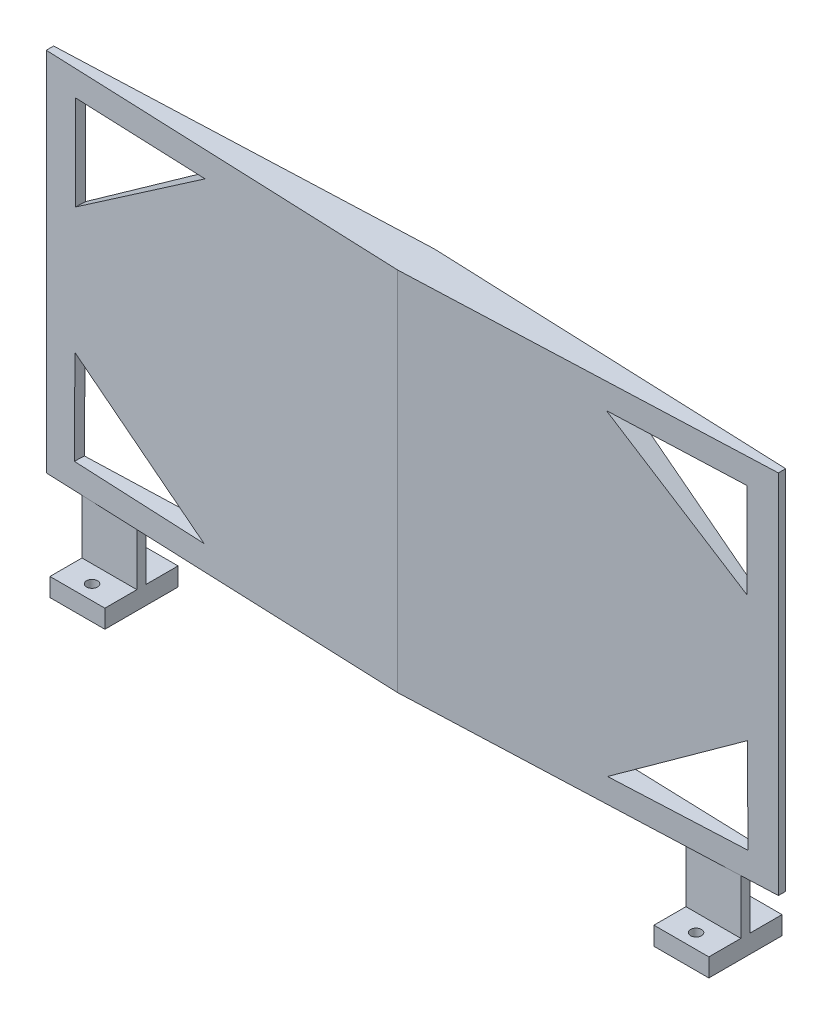
SolidWorks part; units mm, degrees
ref_plane "Front Plane" through (0, 0, 0) normal (0, 0, 1) x (1, 0, 0)
ref_plane "Top Plane" through (0, 0, 0) normal (0, 1, 0) x (1, 0, 0)
ref_plane "Right Plane" through (0, 0, 0) normal (1, 0, 0) x (0, 0, -1)
sketch "Sketch7" plane through (0, 0, 0) normal (0, 1, 0) x (1, 0, 0)
  line L0 (0, 0) -> (-100, 0) construction
  line L1 (-100, 0) -> (78.1251, 0) construction
  line L2 (0, 0) -> (0, 30.674) construction
  line L3 (0, 30.674) -> (0, -32.0574) construction
  line L5 (100, -1) -> (100, 1)
  line L6 (-100, 1) -> (0, 5)
  line L7 (-100, -1) -> (-100, 1)
  line L8 (-100, -1) -> (0, -5)
  line L10 (100, 1) -> (0, 5)
  line L11 (100, -1) -> (0, -5)
  dimension "D1" = 1
  dimension "D2" = 5
  dimension "D3" = 100
extrude "Boss-Extrude4" add sketch "Sketch7" along normal blind 100
sketch "Sketch8" plane through (0, 0, 0) normal (0, -1, 0) x (1, 0, 0)
  line L0 (-100, 0) -> (100, 0) construction
  line L1 (-100, -1) -> (-100, 1) construction
  line L2 (100, 1) -> (100, -1) construction
  line L3 (0, 5) -> (0, -5) construction
  line L9 (-90, 1.25) -> (-75, 1.25)
  line L10 (-90, 1.25) -> (-90, -1.25)
  line L11 (-90, -1.25) -> (-75, -1.25)
  line L12 (-75, 1.25) -> (-75, -1.25)
  line L13 (-90, 1.25) -> (-75, -1.25) construction
  line L14 (-90, -1.25) -> (-75, 1.25) construction
  point P10 (-82.5, 0)
  dimension "D1" = 17.5
  dimension "D2" = 2.5
  dimension "D3" = 15
extrude "Boss-Extrude5" add sketch "Sketch8" along normal blind 15
sketch "Sketch9" plane through (0, -15, 0) normal (0, -1, 0) x (1, 0, 0)
  line L0 (-90, 0) -> (-75, 0) construction
  line L1 (-90, 1.25) -> (-90, -1.25) construction
  line L2 (-75, -1.25) -> (-75, 1.25) construction
  line L3 (-82.5, 1.25) -> (-82.5, -1.25) construction
  line L4 (-75, 1.25) -> (-90, 1.25) construction
  line L5 (-90, -1.25) -> (-75, -1.25) construction
  line L7 (-90, 10) -> (-75, 10)
  line L8 (-90, 10) -> (-90, -10)
  line L9 (-90, -10) -> (-75, -10)
  line L10 (-75, 10) -> (-75, -10)
  line L11 (-90, 10) -> (-75, -10) construction
  line L12 (-90, -10) -> (-75, 10) construction
  point P12 (-82.5, 0)
  dimension "D1" = 15
  dimension "D2" = 20
extrude "Boss-Extrude6" add sketch "Sketch9" along normal blind 5
mirror "Mirror1" about plane through (0, 0, 0) normal (1, 0, 0) of "Boss-Extrude5", "Boss-Extrude6"
sketch "Sketch10" plane through (-0.1997, 0, 4.992) normal (-0.04, 0, 0.9992) x (0.9992, 0, 0.04)
  line L3 (-91.602, 67.2043) -> (-91.602, 93.0576)
  line L4 (-91.602, 93.0576) -> (-54.6698, 93.0576)
  line L5 (-54.6698, 93.0576) -> (-91.602, 67.2043)
  line L6 (0.1998, 99.3176) -> (0.1998, 0) construction
  line L7 (0.1998, 100) -> (0.1998, 0) construction
  line L8 (-99.8801, 50) -> (0.1998, 49.6588) construction
  line L9 (-99.8801, 100) -> (-99.8801, 0) construction
  line L10 (-91.8958, 6.8869) -> (-54.9644, 6.6351)
  line L11 (-91.7195, 32.7397) -> (-91.8958, 6.8869)
  line L12 (-54.9644, 6.6351) -> (-91.7195, 32.7397)
extrude "Cut-Extrude1" cut sketch "Sketch10" against normal up to surface (9.992 mm away)
mirror "Mirror2" about plane through (0, 0, 0) normal (1, 0, 0) of "Cut-Extrude1"
sketch "Sketch11" plane through (0, -15, 0) normal (0, 1, 0) x (1, 0, 0)
  line L0 (-82.5, 10) -> (-82.5, -10) construction
  line L1 (-90, 10) -> (-75, 10) construction
  line L2 (-75, -10) -> (-90, -10) construction
  circle A0 centre (-82.5, 6) radius 1.5
  dimension "D2" = 3
  dimension "D1" = 4
extrude "Cut-Extrude2" cut sketch "Sketch11" against normal up to surface (5 mm away) up to face at (-82.5, -20, 0)
mirror "Mirror3" about plane through (0, 0, 0) normal (0, 0, 1) of "Cut-Extrude2"
mirror "Mirror4" about plane through (0, 0, 0) normal (1, 0, 0) of "Mirror3", "Cut-Extrude2"
